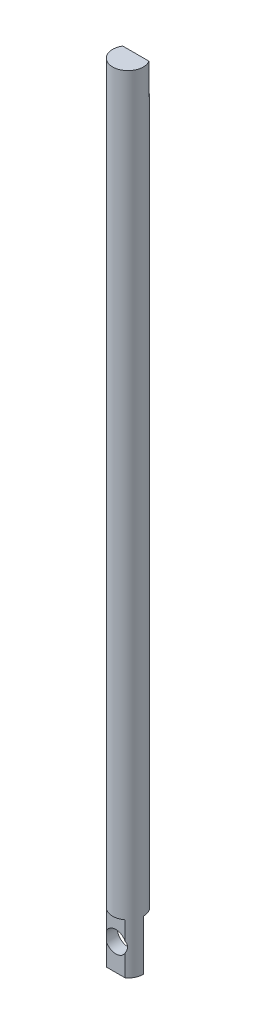
SolidWorks part; units mm, degrees
material "Thornel Mat VMA"
ref_plane "Front Plane" through (0, 0, 0) normal (0, 0, 1) x (1, 0, 0)
ref_plane "Top Plane" through (0, 0, 0) normal (0, 1, 0) x (1, 0, 0)
ref_plane "Right Plane" through (0, 0, 0) normal (1, 0, 0) x (0, 0, -1)
sketch "Sketch1" plane through (0, 0, 0) normal (0, 1, 0) x (1, 0, 0)
  circle A0 centre (0, 0) radius 1.95
  dimension "D1" = 3.9
extrude "Boss-Extrude1" add sketch "Sketch1" along normal mid plane 100
sketch "Sketch2" plane through (0, 0, 0) normal (0, 0, 1) x (1, 0, 0)
  line L0 (1.95, -50) -> (1.95, 50) construction
  line L1 (-1.95, -50) -> (1.95, -50)
  line L2 (-1.95, -50) -> (-1.95, -43.6)
  line L3 (-1.95, -43.6) -> (1.95, -43.6)
  line L4 (1.95, -50) -> (1.95, -43.6)
  line L6 (-1.95, 50) -> (1.95, 50)
  line L7 (-1.95, 50) -> (-1.95, 46)
  line L8 (-1.95, 46) -> (1.95, 46)
  line L9 (1.95, 50) -> (1.95, 46)
  dimension "D1" = 6.4
  dimension "D2" = 4
extrude "Cut-Extrude1" cut sketch "Sketch2" against normal through all
sketch "Sketch3" plane through (0, 0, 0) normal (1, 0, 0) x (0, 0, -1)
  line L0 (-1.95, -50) -> (-1.95, -43.6)
  line L1 (-1.95, 50) -> (-1.95, -50) construction
  line L2 (-1.95, -43.6) -> (-1.55, -43.6)
  line L3 (-1.55, -43.6) -> (-1.55, -50)
  line L4 (-1.95, -50) -> (0, -50) construction
  line L5 (-1.55, -50) -> (-1.95, -50)
  dimension "D1" = 6.4
  dimension "D2" = 0.4
extrude "Cut-Extrude2" cut sketch "Sketch3" against normal through all both and the other way through all
sketch "Sketch4" plane through (0, 0, 0) normal (0, 0, -1) x (-1, 0, 0)
  line L1 (1.95, -50) -> (-1.95, -50) construction
  line L2 (-1.95, -50) -> (-1.95, -43.6) construction
  circle A0 centre (0, -46.6) radius 1.35
  point P2 (0, 0)
  point P5 (0, -50)
  point P6 (0, -46.6)
  dimension "D1" = 2.7
  dimension "D2" = 3.4
  dimension "D3" = 1.95
extrude "Cut-Extrude3" cut sketch "Sketch4" against normal through all both and the other way through all
sketch "Sketch5" plane through (0, 0, 0) normal (0, 0, -1) x (-1, 0, 0)
  line L0 (1.95, 46) -> (-1.95, 46) construction
  circle A0 centre (0, 45.89) radius 1.235
  point P4 (0, 0)
  dimension "D1" = 2.47
  dimension "D2" = 0.11
extrude "Cut-Extrude4" cut sketch "Sketch5" along normal through all
sketch "Sketch6" plane through (0, 0, 0) normal (0, 0, -1) x (-1, 0, 0)
  line L5 (-1.95, 46) -> (-1.2301, 46)
  line L6 (1.2301, 46) -> (1.95, 46)
  line L7 (1.95, 46) -> (1.95, 50)
  line L8 (1.95, 50) -> (-1.95, 50)
  line L9 (-1.95, 50) -> (-1.95, 46)
  line L10 (-1.95, 46) -> (-1.2301, 46)
  line L11 (1.2301, 46) -> (1.95, 46)
  line L12 (1.95, 46) -> (1.95, 50)
  line L13 (1.95, 50) -> (-1.95, 50)
  line L14 (-1.95, 50) -> (-1.95, 46)
  arc A0 (1.2301, 46) -> (-1.2301, 46) centre (0, 45.89) ccw
  arc A1 (-1.2301, 46) -> (1.2301, 46) centre (0, 45.89) ccw
  dimension "D1" = 0
extrude "Boss-Extrude2" add sketch "Sketch6" along normal blind 1
sketch "Sketch7" plane through (0, 46, 0) normal (0, -1, 0) x (1, 0, 0)
  line L0 (1.95, -1) -> (1.95, 0) construction
  line L1 (1.6741, -1) -> (1.95, -1) construction
  line L2 (-1.95, -1) -> (-1.6741, -1) construction
  line L3 (-1.95, 0) -> (-1.95, -1) construction
  line L4 (1.95, -1) -> (1.95, 0)
  line L5 (1.6741, -1) -> (1.95, -1)
  line L6 (-1.95, -1) -> (-1.6741, -1)
  line L7 (-1.95, 0) -> (-1.95, -1)
  arc A0 (1.6741, -1) -> (1.95, 0) centre (0, 0) ccw construction
  arc A1 (-1.95, 0) -> (-1.6741, -1) centre (0, 0) ccw construction
  arc A2 (1.6741, -1) -> (1.95, 0) centre (0, 0) ccw
  arc A3 (-1.95, 0) -> (-1.6741, -1) centre (0, 0) ccw
extrude "Cut-Extrude5" cut sketch "Sketch7" against normal through all
